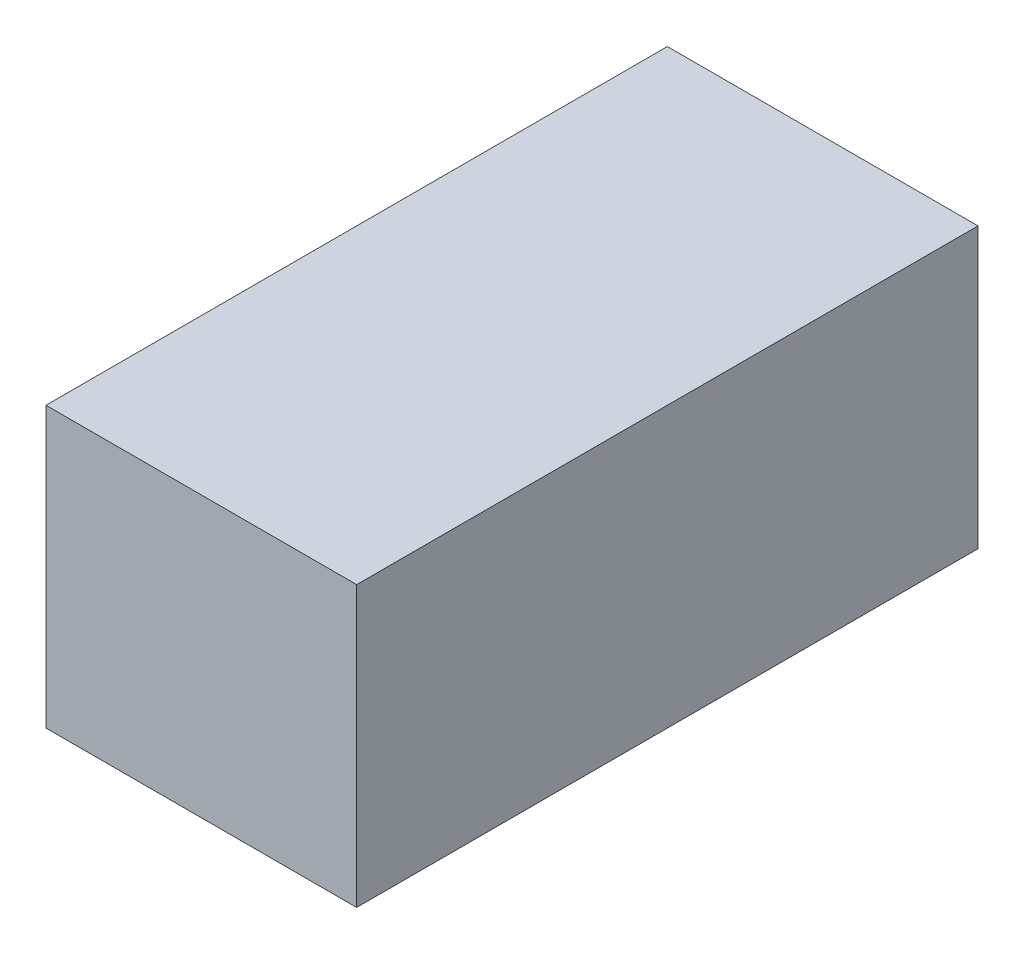
SolidWorks part; units mm, degrees
ref_plane "Front Plane" through (0, 0, 0) normal (0, 0, 1) x (1, 0, 0)
ref_plane "Top Plane" through (0, 0, 0) normal (0, 1, 0) x (1, 0, 0)
ref_plane "Right Plane" through (0, 0, 0) normal (1, 0, 0) x (0, 0, -1)
other "Center of Mass"
sketch "Sketch1" plane through (0, 0, 0) normal (0, 0, 1) x (1, 0, 0)
  line L1 (-100, -90) -> (100, -90)
  line L2 (-100, -90) -> (-100, 90)
  line L3 (-100, 90) -> (100, 90)
  line L4 (100, -90) -> (100, 90)
  line L5 (-100, -90) -> (100, 90) construction
  line L6 (-100, 90) -> (100, -90) construction
  point P0 (0, 0)
  dimension "D1" = 180
  dimension "D2" = 200
extrude "Boss-Extrude1" add sketch "Sketch1" along normal blind 400
sketch "Sketch2" plane through (0, 90, 0) normal (0, 1, 0) x (1, 0, 0)
  point P0 (0, 3.2683)
sketch "Sketch3" plane through (-100, 0, 0) normal (-1, 0, 0) x (0, 0, 1)
  line L0 (400, 90) -> (400, -90) construction
  point P0 (400, 0)
